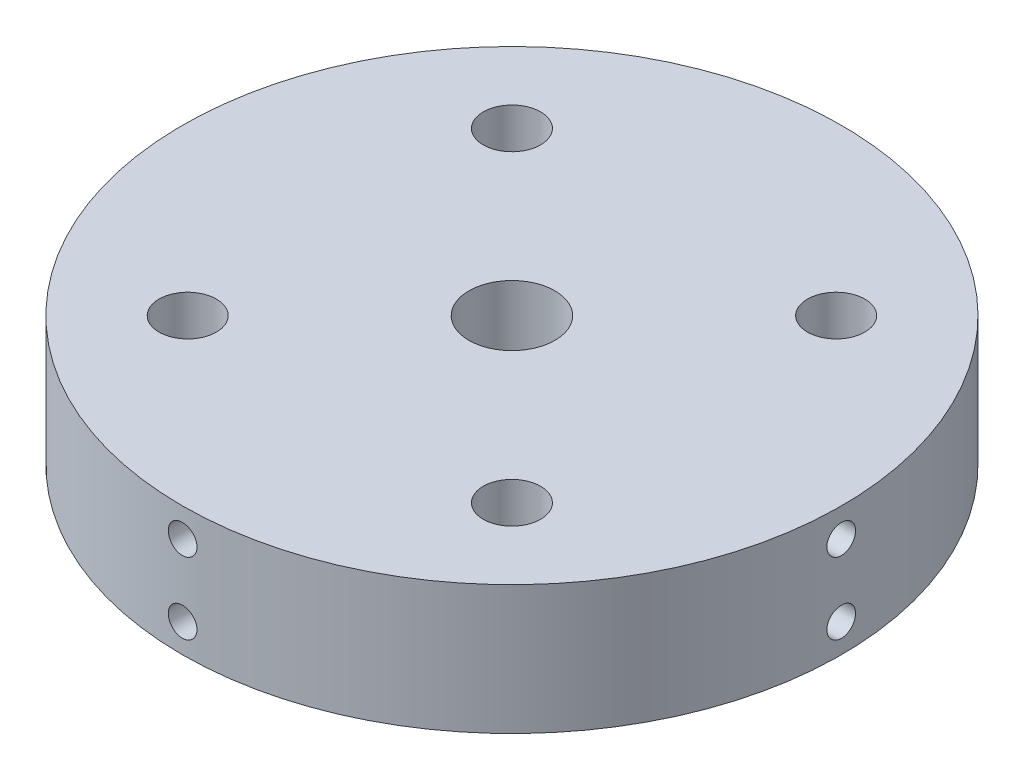
SolidWorks part; units mm, degrees
material "6061-T6 (SS)"
ref_plane "Front Plane" through (0, 0, 0) normal (0, 0, 1) x (1, 0, 0)
ref_plane "Top Plane" through (0, 0, 0) normal (0, 1, 0) x (1, 0, 0)
ref_plane "Right Plane" through (0, 0, 0) normal (1, 0, 0) x (0, 0, -1)
sketch "Sketch1" plane through (0, 0, 0) normal (0, 1, 0) x (1, 0, 0)
  circle A0 centre (0, 0) radius 73.025
  dimension "D1" = 146.05
extrude "Boss-Extrude1" add sketch "Sketch1" along normal blind 28.575
sketch "Sketch2" plane through (0, 28.575, 0) normal (0, 1, 0) x (1, 0, 0)
  circle A0 centre (0, 0) radius 9.525
  dimension "D1" = 19.05
extrude "Cut-Extrude1" cut sketch "Sketch2" against normal through all
ref_plane "Plane1" through (0, 0, 73.025) normal (0, 0, 1) x (1, 0, 0)
ref_plane "Plane2" through (0, 0, -73.025) normal (0, 0, 1) x (1, 0, 0)
sketch "Sketch30" plane through (0, 0, 73.025) normal (0, 0, 1) x (1, 0, 0)
  line L0 (0, 30.5674) -> (0, -2.7265) construction
  line L1 (73.025, 28.575) -> (-73.025, 28.575) construction
  circle A0 centre (0, 22.225) radius 3.175
  circle A1 centre (0, 6.35) radius 3.175
  dimension "D1" = 6.35
  dimension "D2" = 6.35
  dimension "D3" = 15.875
  dimension "D4" = 6.35
extrude "Cut-Extrude2" cut sketch "Sketch30" against normal blind 25.4
pattern_circular "CirPattern3" count 4 over 360 about axis through (0, 0, 0) along (0, 1, 0) of "Cut-Extrude2"
sketch "Sketch31" plane through (0, 28.575, 0) normal (0, 1, 0) x (1, 0, 0)
  line L0 (0, 73.025) -> (0, -73.025) construction
  line L1 (-73.025, 0) -> (73.025, 0) construction
  line L2 (51.6365, 51.6365) -> (-51.6365, -51.6365) construction
  line L3 (-51.6365, 51.6365) -> (51.6365, -51.6365) construction
  circle A0 centre (0, 0) radius 73.025 construction
  circle A1 centre (35.921, 35.921) radius 6.35
  dimension "D4" = 12.7
  dimension "D1" = 50.8
  dimension "D2" = 45
  dimension "D3" = 45
extrude "Cut-Extrude3" cut sketch "Sketch31" against normal through all
pattern_circular "CirPattern4" count 4 over 360 about axis through (0, 0, 0) along (0, 1, 0) of "Cut-Extrude3"
